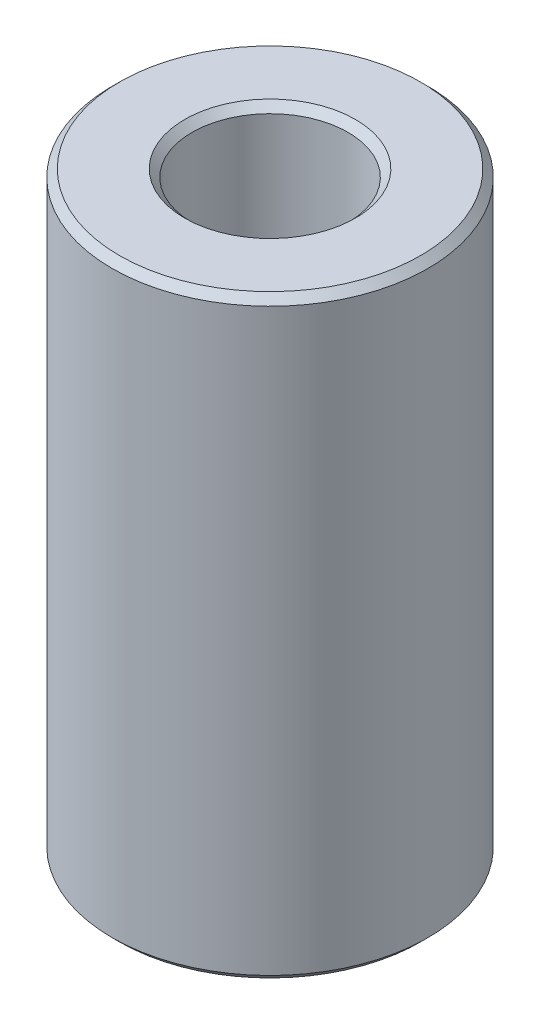
SolidWorks part; units mm, degrees
ref_plane "Front Plane" through (0, 0, 0) normal (0, 0, 1) x (1, 0, 0)
ref_plane "Top Plane" through (0, 0, 0) normal (0, 1, 0) x (1, 0, 0)
ref_plane "Right Plane" through (0, 0, 0) normal (1, 0, 0) x (0, 0, -1)
sketch "Sketch1" plane through (0, 0, 0) normal (0, 1, 0) x (1, 0, 0)
  circle A0 centre (0, 0) radius 2.1
  circle A1 centre (0, 0) radius 4.25
  dimension "D1" = 4.2
  dimension "D2" = 8.5
extrude "Boss-Extrude1" add sketch "Sketch1" along normal blind 16
chamfer "Chamfer1" distance 0.2 angle 45 4 edges at (0, 16, 2.1) (0, 16, 4.25) (0, 0, 2.1) (0, 0, 4.25)
